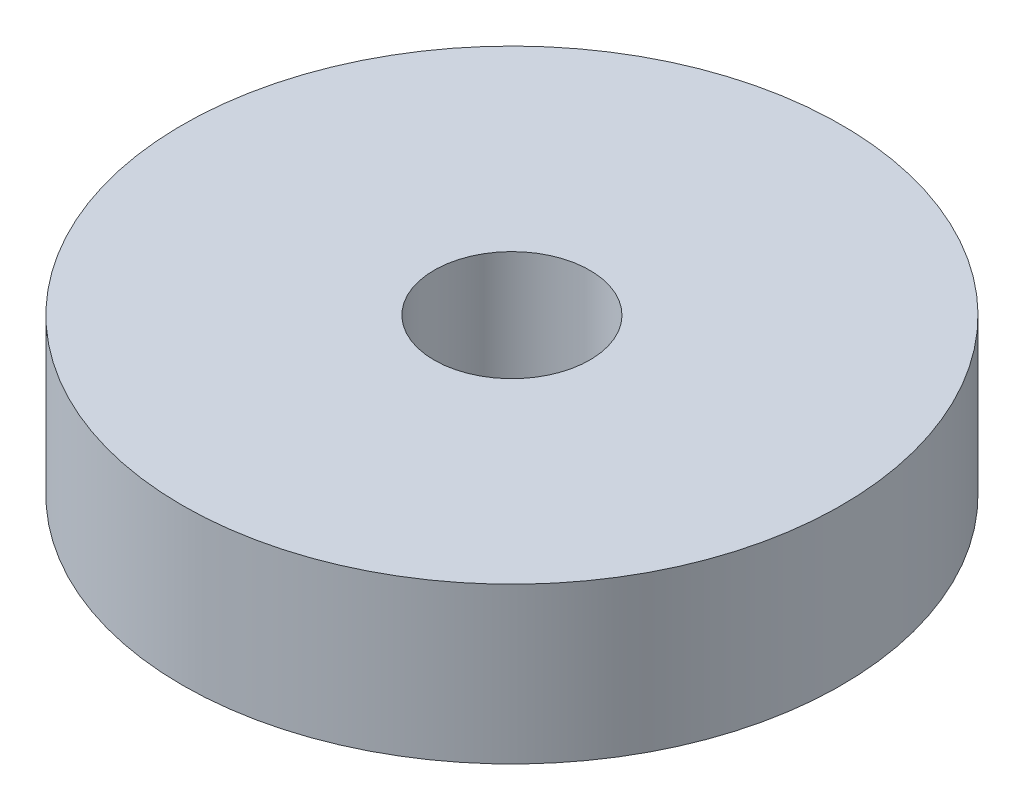
SolidWorks part; units mm, degrees
ref_plane "Front Plane" through (0, 0, 0) normal (0, 0, 1) x (1, 0, 0)
ref_plane "Top Plane" through (0, 0, 0) normal (0, 1, 0) x (1, 0, 0)
ref_plane "Right Plane" through (0, 0, 0) normal (1, 0, 0) x (0, 0, -1)
sketch "Sketch1" plane through (0, 0, 0) normal (0, 1, 0) x (1, 0, 0)
  circle A0 centre (0, 0) radius 3
  circle A1 centre (0, 0) radius 12.7
  dimension "D1" = 6
  dimension "D2" = 25.4
extrude "Boss-Extrude1" add sketch "Sketch1" along normal blind 6
